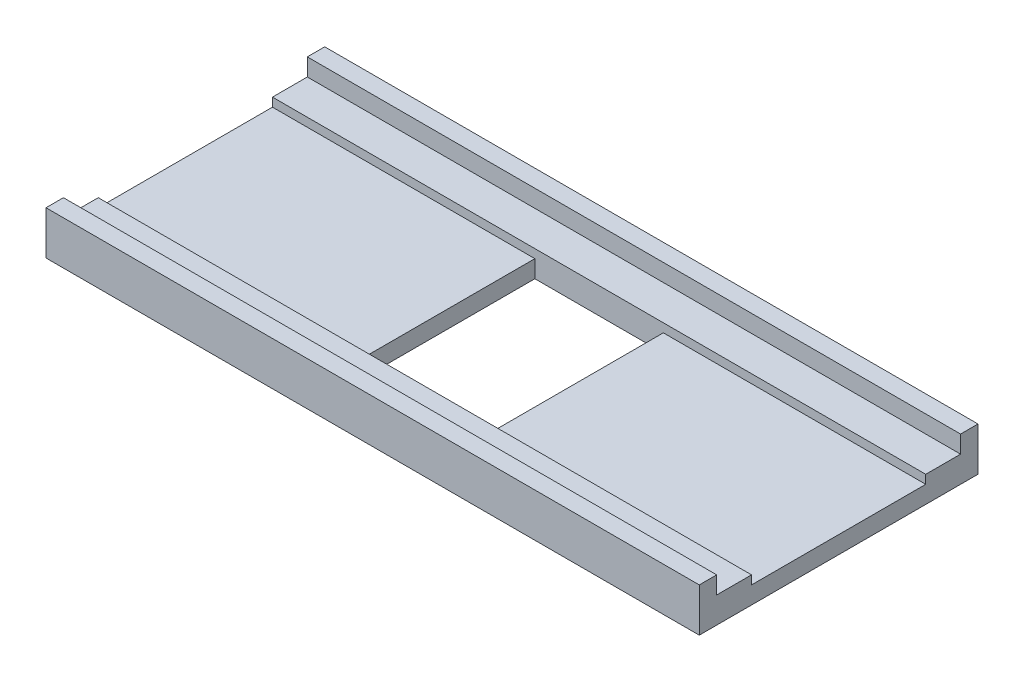
SolidWorks part; units mm, degrees
material "1345 Alloy"
ref_plane "Front Plane" through (0, 0, 0) normal (0, 0, 1) x (1, 0, 0)
ref_plane "Top Plane" through (0, 0, 0) normal (0, 1, 0) x (1, 0, 0)
ref_plane "Right Plane" through (0, 0, 0) normal (1, 0, 0) x (0, 0, -1)
sketch "Sketch1" plane through (0, 0, 0) normal (0, 1, 0) x (1, 0, 0)
  line L1 (-37.5, 16) -> (37.5, 16)
  line L2 (-37.5, 16) -> (-37.5, -16)
  line L3 (-37.5, -16) -> (37.5, -16)
  line L4 (37.5, 16) -> (37.5, -16)
  line L5 (-37.5, 16) -> (37.5, -16) construction
  line L6 (-37.5, -16) -> (37.5, 16) construction
  point P0 (0, 0)
  dimension "D1" = 32
  dimension "D2" = 75
extrude "Boss-Extrude1" add sketch "Sketch1" along normal blind 3
sketch "Sketch2" plane through (0, 3, 0) normal (0, 1, 0) x (1, 0, 0)
  line L0 (37.5, -16) -> (37.5, 16) construction
  line L1 (-37.5, 16) -> (37.5, 16)
  line L2 (-37.5, 16) -> (-37.5, 14)
  line L3 (-37.5, 14) -> (37.5, 14)
  line L4 (37.5, 16) -> (37.5, 14)
  dimension "D1" = 2
extrude "Boss-Extrude2" add sketch "Sketch2" along normal blind 2
sketch "Sketch3" plane through (0, 3, 0) normal (0, 1, 0) x (1, 0, 0)
  line L0 (37.5, -16) -> (37.5, 14) construction
  line L1 (-37.5, -16) -> (37.5, -16)
  line L2 (-37.5, -16) -> (-37.5, -14)
  line L3 (-37.5, -14) -> (37.5, -14)
  line L4 (37.5, -16) -> (37.5, -14)
  dimension "D1" = 2
extrude "Boss-Extrude3" add sketch "Sketch3" along normal up to surface (2 mm away) up to face at (0, 5, -15)
sketch "Sketch6" plane through (0, 3, 0) normal (0, 1, 0) x (1, 0, 0)
  line L0 (-37.5, 16) -> (-37.5, -16) construction
  line L2 (-37.5, -16) -> (37.5, -16) construction
  line L3 (37.5, -14) -> (37.5, 14) construction
  line L4 (37.5, -16) -> (37.5, 16) construction
  line L5 (37.5, 16) -> (-37.5, 16) construction
  line L7 (-37.5, 0) -> (37.5, 0) construction
  line L8 (0, 16) -> (0, -8.5) construction
  line L10 (-7.375, 10) -> (7.375, 10)
  line L11 (-7.375, 10) -> (-7.375, -10)
  line L12 (-7.375, -10) -> (7.375, -10)
  line L13 (7.375, 10) -> (7.375, -10)
  line L14 (-7.375, 10) -> (7.375, -10) construction
  line L15 (-7.375, -10) -> (7.375, 10) construction
  point P17 (0, 0)
  dimension "D1" = 14.75
  dimension "D2" = 20
  dimension "D3" = 6
extrude "Cut-Extrude3" cut sketch "Sketch6" against normal through all
sketch "Sketch7" plane through (0, 3, 0) normal (0, 1, 0) x (1, 0, 0)
  line L0 (-37.5, 14) -> (-37.5, -14) construction
  line L1 (-37.5, 10) -> (37.5, 10)
  line L2 (-37.5, 10) -> (-37.5, -10)
  line L3 (-37.5, -10) -> (37.5, -10)
  line L4 (37.5, 10) -> (37.5, -10)
  line L5 (37.5, -14) -> (37.5, 14) construction
  line L6 (7.375, 10) -> (-7.375, 10) construction
  line L7 (-7.375, -10) -> (7.375, -10) construction
extrude "Cut-Extrude4" cut sketch "Sketch7" against normal blind 1
